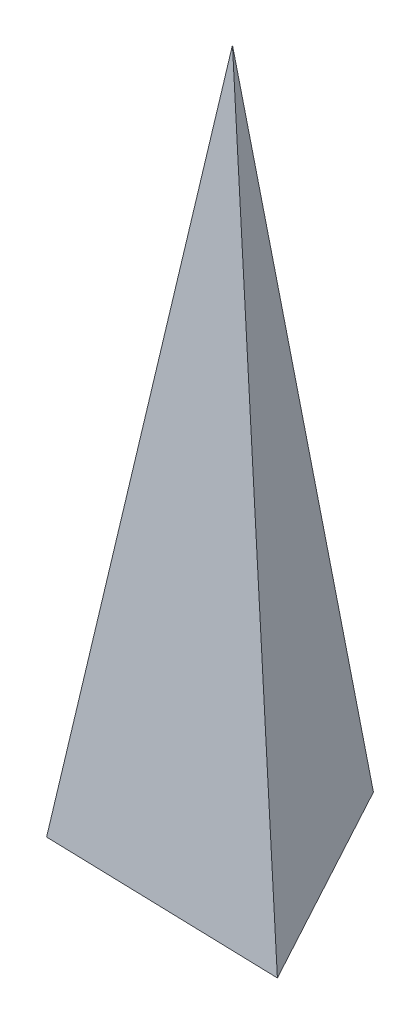
SolidWorks part; units mm, degrees
ref_plane "前视基准面" through (0, 0, 0) normal (0, 0, 1) x (1, 0, 0)
ref_plane "上视基准面" through (0, 0, 0) normal (0, 1, 0) x (1, 0, 0)
ref_plane "右视基准面" through (0, 0, 0) normal (1, 0, 0) x (0, 0, -1)
sketch "草图1" plane through (0, 0, 0) normal (0, 1, 0) x (1, 0, 0)
  line L1 (12.2926, -7.5647) -> (0.4049, 14.4281)
  line L2 (0.4049, 14.4281) -> (-12.6975, -6.8634)
  line L3 (-12.6975, -6.8634) -> (12.2926, -7.5647)
  circle A0 centre (0, 0) radius 7.2169 construction
extrude "凸台-拉伸1" add sketch "草图1" along normal blind 75 draft 5.49
